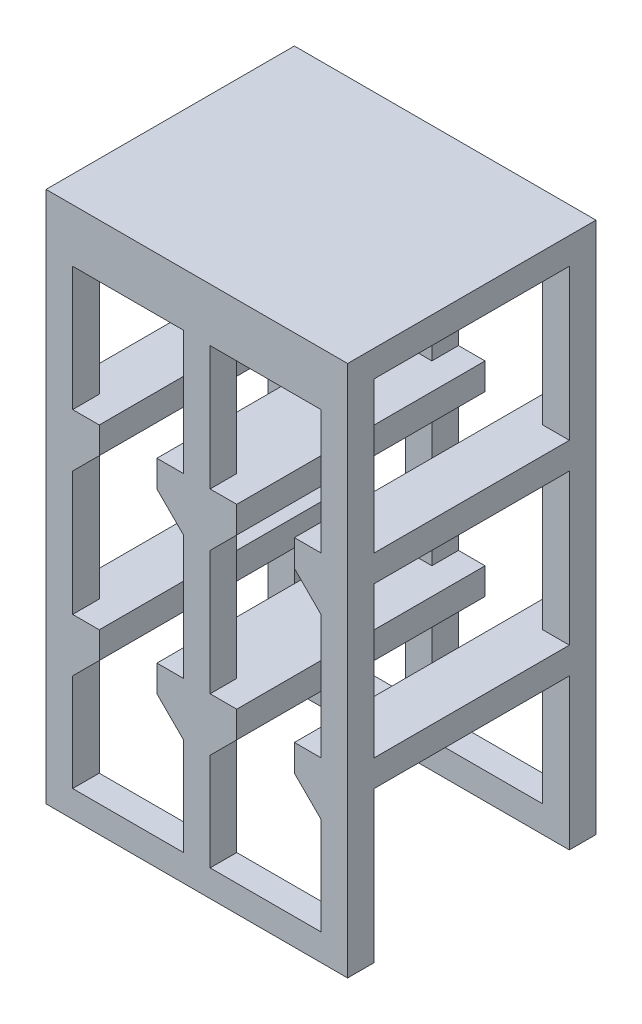
SolidWorks part; units mm, degrees
material "6061 Alloy"
ref_plane "Front Plane" through (0, 0, 0) normal (0, 0, 1) x (1, 0, 0)
ref_plane "Top Plane" through (0, 0, 0) normal (0, 1, 0) x (1, 0, 0)
ref_plane "Right Plane" through (0, 0, 0) normal (1, 0, 0) x (0, 0, -1)
sketch "Sketch1" plane through (0, 0, 0) normal (0, 1, 0) x (1, 0, 0)
  line L1 (-170, 140) -> (170, 140)
  line L2 (-170, 140) -> (-170, -140)
  line L3 (-170, -140) -> (170, -140)
  line L4 (170, 140) -> (170, -140)
  line L5 (-170, 140) -> (170, -140) construction
  line L6 (-170, -140) -> (170, 140) construction
  point P0 (0, 0)
  dimension "D1" = 340
  dimension "D2" = 280
extrude "Boss-Extrude1" add sketch "Sketch1" along normal blind 600
sketch "Sketch4" plane through (170, 0, 0) normal (1, 0, 0) x (0, 0, -1)
  line L0 (-140, 0) -> (140, 0) construction
  line L1 (-110, 570) -> (110, 570)
  line L2 (-110, 570) -> (-110, 400)
  line L3 (-110, 400) -> (110, 400)
  line L4 (110, 570) -> (110, 400)
  line L5 (-110, 570) -> (110, 400) construction
  line L6 (-110, 400) -> (110, 570) construction
  line L7 (-110, 370) -> (110, 370)
  line L8 (-110, 370) -> (-110, 200)
  line L9 (-110, 200) -> (110, 200)
  line L10 (110, 370) -> (110, 200)
  line L11 (-110, 370) -> (110, 200) construction
  line L12 (-110, 200) -> (110, 370) construction
  line L13 (-110, 170) -> (110, 170)
  line L14 (-110, 170) -> (-110, 0)
  line L15 (-110, 0) -> (110, 0)
  line L16 (110, 170) -> (110, 0)
  line L17 (-110, 170) -> (110, 0) construction
  line L18 (-110, 0) -> (110, 170) construction
  line L19 (-140, 170) -> (-110, 170) construction
  line L20 (-140, 600) -> (-140, 0) construction
  line L21 (110, 170) -> (140, 170) construction
  line L22 (140, 600) -> (140, 0) construction
  line L23 (-110, 200) -> (-110, 170) construction
  line L24 (-110, 400) -> (-110, 370) construction
  point P0 (0, 485)
  point P5 (0, 285)
  point P10 (0, 85)
  dimension "D1" = 200
  dimension "D2" = 200
  dimension "D3" = 30
extrude "Cut-Extrude1" cut sketch "Sketch4" against normal through all both and the other way through all
sketch "Sketch6" plane through (0, 0, 140) normal (0, 0, 1) x (1, 0, 0)
  line L0 (-170, 0) -> (170, 0) construction
  line L1 (-140, 540) -> (-15, 540)
  line L2 (-140, 540) -> (-140, 370)
  line L3 (-140, 370) -> (-15, 370)
  line L4 (-15, 540) -> (-15, 370)
  line L5 (-140, 540) -> (-15, 370) construction
  line L6 (-140, 370) -> (-15, 540) construction
  line L7 (15, 540) -> (140, 540)
  line L8 (15, 540) -> (15, 370)
  line L9 (15, 370) -> (140, 370)
  line L10 (140, 540) -> (140, 370)
  line L11 (15, 540) -> (140, 370) construction
  line L12 (15, 370) -> (140, 540) construction
  line L13 (-140, 340) -> (-15, 340)
  line L14 (-140, 340) -> (-140, 170)
  line L15 (-140, 170) -> (-15, 170)
  line L16 (-15, 340) -> (-15, 170)
  line L17 (-140, 340) -> (-15, 170) construction
  line L18 (-140, 170) -> (-15, 340) construction
  line L19 (15, 340) -> (140, 340)
  line L20 (15, 340) -> (15, 170)
  line L21 (15, 170) -> (140, 170)
  line L22 (140, 340) -> (140, 170)
  line L23 (15, 340) -> (140, 170) construction
  line L24 (15, 170) -> (140, 340) construction
  line L25 (-140, 140) -> (-15, 140)
  line L26 (-140, 140) -> (-140, 30)
  line L27 (-140, 30) -> (-15, 30)
  line L28 (-15, 140) -> (-15, 30)
  line L29 (-140, 140) -> (-15, 30) construction
  line L30 (-140, 30) -> (-15, 140) construction
  line L31 (15, 140) -> (140, 140)
  line L32 (15, 140) -> (15, 30)
  line L33 (15, 30) -> (140, 30)
  line L34 (140, 140) -> (140, 30)
  line L35 (15, 140) -> (140, 30) construction
  line L36 (15, 30) -> (140, 140) construction
  line L37 (-170, 370) -> (-140, 370) construction
  line L38 (-170, 340) -> (-140, 340) construction
  line L39 (-15, 370) -> (15, 370) construction
  line L40 (-15, 340) -> (15, 340) construction
  line L41 (140, 370) -> (170, 370) construction
  line L42 (140, 340) -> (170, 340) construction
  line L43 (15, 370) -> (15, 340) construction
  line L44 (15, 170) -> (15, 140) construction
  line L45 (-15, 370) -> (-15, 340) construction
  line L46 (-15, 170) -> (-15, 140) construction
  line L47 (-170, 600) -> (-170, 0) construction
  line L48 (170, 600) -> (170, 0) construction
  line L49 (15, 30) -> (15, 0) construction
  line L50 (-140, 170) -> (-140, 140)
  line L51 (-15, 30) -> (-15, 0) construction
  line L52 (-77.5, 540) -> (-77.5, 30) construction
  line L53 (-140, 370) -> (-140, 340)
  line L54 (-140, 200) -> (-110, 200)
  line L55 (-140, 200) -> (-140, 170)
  line L56 (-140, 170) -> (-110, 170)
  line L57 (-110, 200) -> (-110, 170)
  line L58 (-140, 200) -> (-110, 170) construction
  line L59 (-140, 170) -> (-110, 200) construction
  line L60 (-140, 340) -> (-110, 370)
  line L61 (-140, 140) -> (-110, 170)
  line L62 (-140, 400) -> (-110, 400)
  line L63 (-140, 400) -> (-140, 370)
  line L64 (-140, 370) -> (-110, 370)
  line L65 (-110, 400) -> (-110, 370)
  line L66 (-140, 400) -> (-110, 370) construction
  line L67 (-140, 370) -> (-110, 400) construction
  line L68 (0, 600) -> (0, 0) construction
  line L69 (-170, 600) -> (170, 600) construction
  line L70 (-15, 370) -> (-15, 340)
  line L71 (-45, 370) -> (-15, 340)
  line L72 (15, 370) -> (15, 340)
  line L73 (15, 340) -> (45, 370)
  line L74 (140, 370) -> (140, 340)
  line L75 (110, 370) -> (140, 340)
  line L76 (140, 170) -> (140, 140)
  line L77 (110, 170) -> (140, 140)
  line L78 (15, 170) -> (15, 140)
  line L79 (45, 170) -> (15, 140)
  line L80 (-15, 170) -> (-15, 140)
  line L81 (-45, 170) -> (-15, 140)
  line L83 (-45, 400) -> (-15, 400)
  line L84 (-45, 400) -> (-45, 370)
  line L85 (-45, 370) -> (-15, 370)
  line L86 (-15, 400) -> (-15, 370)
  line L87 (-45, 400) -> (-15, 370) construction
  line L88 (-45, 370) -> (-15, 400) construction
  line L89 (110, 400) -> (140, 400)
  line L90 (110, 400) -> (110, 370)
  line L91 (110, 370) -> (140, 370)
  line L92 (140, 400) -> (140, 370)
  line L93 (110, 400) -> (140, 370) construction
  line L94 (110, 370) -> (140, 400) construction
  line L95 (15, 400) -> (45, 400)
  line L96 (15, 400) -> (15, 370)
  line L97 (15, 370) -> (45, 370)
  line L98 (45, 400) -> (45, 370)
  line L99 (15, 400) -> (45, 370) construction
  line L100 (15, 370) -> (45, 400) construction
  line L101 (-45, 200) -> (-15, 200)
  line L102 (-45, 200) -> (-45, 170)
  line L103 (-45, 170) -> (-15, 170)
  line L104 (-15, 200) -> (-15, 170)
  line L105 (-45, 200) -> (-15, 170) construction
  line L106 (-45, 170) -> (-15, 200) construction
  line L107 (15, 200) -> (45, 200)
  line L108 (15, 200) -> (15, 170)
  line L109 (15, 170) -> (45, 170)
  line L110 (45, 200) -> (45, 170)
  line L111 (15, 200) -> (45, 170) construction
  line L112 (15, 170) -> (45, 200) construction
  line L113 (110, 200) -> (140, 200)
  line L114 (110, 200) -> (110, 170)
  line L115 (110, 170) -> (140, 170)
  line L116 (140, 200) -> (140, 170)
  line L117 (110, 200) -> (140, 170) construction
  line L118 (110, 170) -> (140, 200) construction
  point P0 (-77.5, 455)
  point P5 (77.5, 455)
  point P10 (-77.5, 255)
  point P14 (125, 385)
  point P15 (77.5, 255)
  point P20 (-77.5, 85)
  point P25 (77.5, 85)
  point P29 (30, 385)
  point P38 (-125, 385)
  point P42 (-125, 185)
  point P78 (-30, 185)
  point P87 (30, 185)
  point P92 (125, 185)
  point P93 (-30, 385)
  dimension "D1" = 170
  dimension "D2" = 200
  dimension "D3" = 30
  dimension "D4" = 30
  dimension "D5" = 45
  dimension "D6" = 45
  dimension "D7" = 30
  dimension "D8" = 45
  dimension "D9" = 45
  dimension "D10" = 45
  dimension "D11" = 45
  dimension "D12" = 45
  dimension "D13" = 45
extrude "Cut-Extrude3" cut sketch "Sketch6" against normal through all both and the other way through all contours L84 L83 L4 L1 L2 L62 L65 L3 | L95 L98 L9 L90 L89 L10 L7 L8 | L114 L113 L22 L19 L20 L107 L110 L21 | L102 L101 L16 L13 L14 L54 L57 L15 | L28 L25 L26 L27 | L34 L31 L32 L33 | L81 L15 L61 L25 | L21 L79 L31 L77 | L75 L9 L73 L19 | L71 L3 L60 L13
